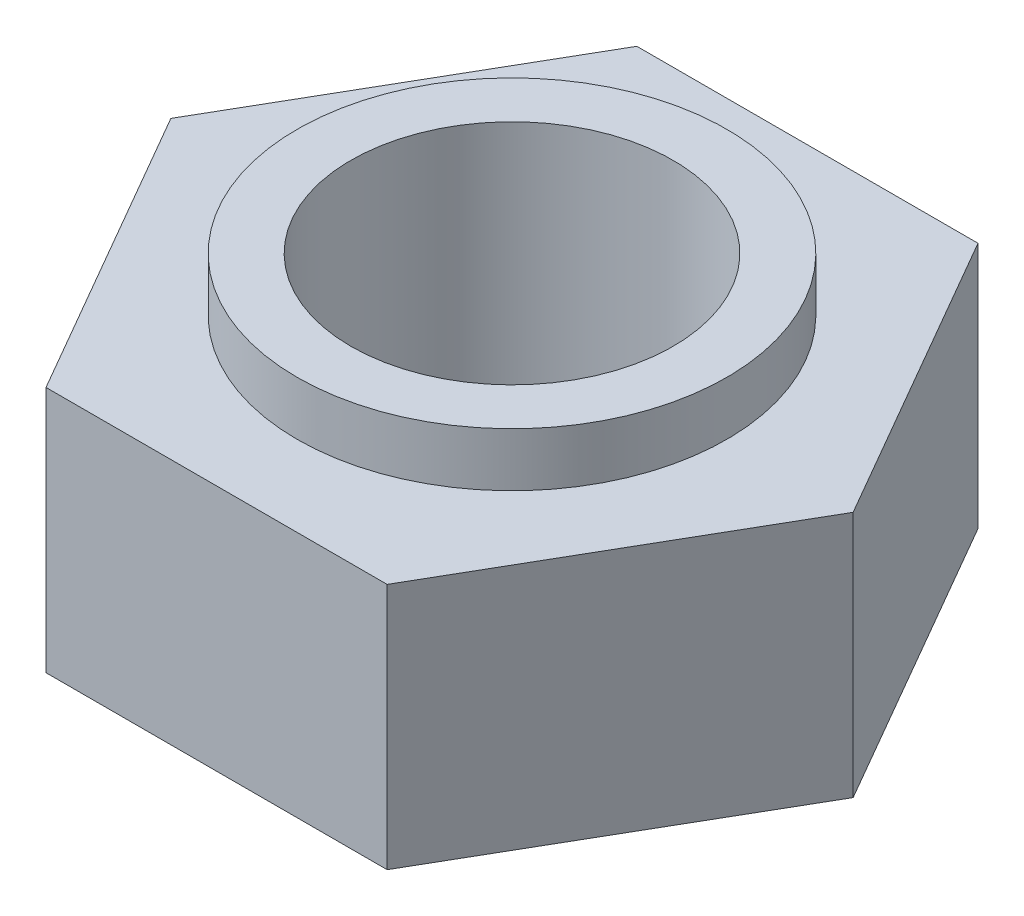
SolidWorks part; units mm, degrees
material "1060 Alloy"
ref_plane "Front Plane" through (0, 0, 0) normal (0, 0, 1) x (1, 0, 0)
ref_plane "Top Plane" through (0, 0, 0) normal (0, 1, 0) x (1, 0, 0)
ref_plane "Right Plane" through (0, 0, 0) normal (1, 0, 0) x (0, 0, -1)
sketch "Sketch1" plane through (0, 0, 0) normal (0, 1, 0) x (1, 0, 0)
  line L1 (3.1754, 0) -> (1.5877, 2.75)
  line L2 (1.5877, 2.75) -> (-1.5877, 2.75)
  line L3 (-1.5877, 2.75) -> (-3.1754, 0)
  line L4 (-3.1754, 0) -> (-1.5877, -2.75)
  line L5 (-1.5877, -2.75) -> (1.5877, -2.75)
  line L6 (1.5877, -2.75) -> (3.1754, 0)
  circle A0 centre (0, 0) radius 2.75 construction
  circle A1 centre (0, 0) radius 1.5
  dimension "D1" = 5.5
  dimension "D2" = 3
extrude "Boss-Extrude1" add sketch "Sketch1" along normal blind 2.3
sketch "Sketch2" plane through (0, 2.3, 0) normal (0, 1, 0) x (1, 0, 0)
  circle A0 centre (0, 0) radius 2
  circle A1 centre (0, 0) radius 1.5
extrude "Boss-Extrude2" add sketch "Sketch2" along normal blind 0.5
